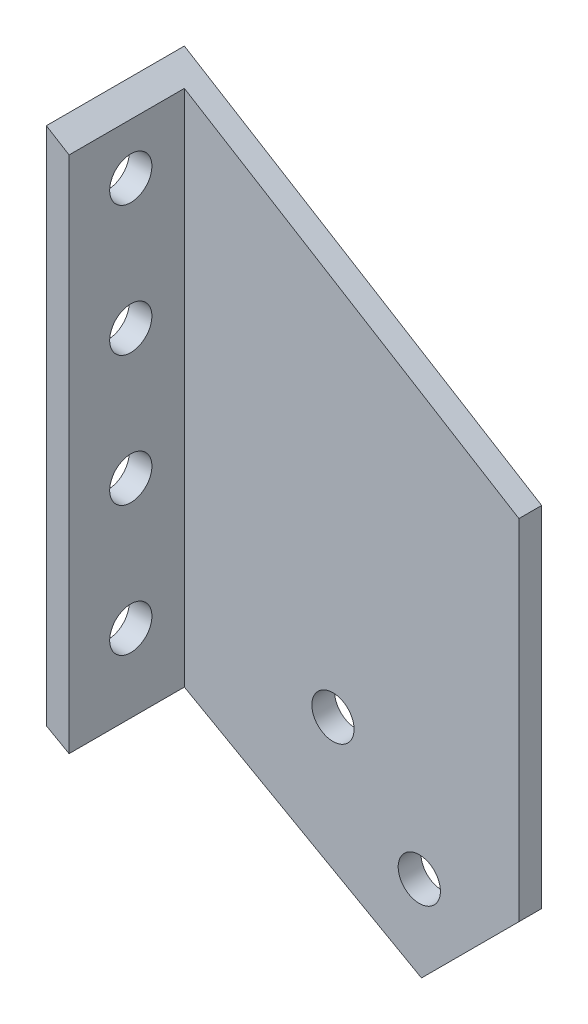
SolidWorks part; units mm, degrees
ref_plane "前视基准面" through (0, 0, 0) normal (0, 0, 1) x (1, 0, 0)
ref_plane "上视基准面" through (0, 0, 0) normal (0, 1, 0) x (1, 0, 0)
ref_plane "右视基准面" through (0, 0, 0) normal (1, 0, 0) x (0, 0, -1)
sketch "草图1" plane through (0, 0, 0) normal (0, 0, 1) x (1, 0, 0)
  line L0 (-1188.0651, 85.2964) -> (48811.9349, 85.2964) construction
  line L1 (-188.0651, -994.7583) -> (-188.0651, 49005.2417) construction
  line L2 (-1173.1343, -49.7036) -> (48826.8657, -49.7036) construction
  line L3 (-148.5651, -1041.5004) -> (-148.5651, 48958.4996) construction
  line L4 (-1169.9539, -234.7036) -> (48830.0461, -234.7036) construction
  line L5 (71.4349, -49.7036) -> (71.4349, -264.7036)
  line L6 (11.4349, -1089.7199) -> (11.4349, 48910.2801) construction
  line L7 (-972.3331, -324.7036) -> (49027.6669, -324.7036) construction
  line L8 (71.4349, -264.7036) -> (11.4349, -324.7036)
  line L9 (11.4349, -324.7036) -> (-148.5651, -234.7036)
  line L10 (-148.5651, -234.7036) -> (-148.5651, 85.2964)
  line L11 (-148.5651, 85.2964) -> (71.4349, -49.7036)
  line L12 (1811.9349, -49.7036) -> (1811.9349, -2299.7036) construction
  line L13 (1811.9349, -2299.7036) -> (-188.0651, -49.7036) construction
  circle A0 centre (-43.0651, -212.8286) radius 13
  circle A1 centre (10.084, -272.6213) radius 13
  point P15 (11.4349, -324.7036)
  point P17 (1811.9349, -49.7036)
  point P21 (-188.0651, -49.7036)
  point P24 (-43.0651, -212.8286)
  point P26 (10.084, -272.6213)
  dimension "D13" = 26
  dimension "D1" = 135
  dimension "D2" = 39.5
  dimension "D3" = 185
  dimension "D4" = 215
  dimension "D5" = 160
  dimension "D6" = 60
  dimension "D7" = 60
  dimension "D8" = 2000
  dimension "D9" = 2250
  dimension "D10" = 145
  dimension "D11" = 80
extrude "凸台-拉伸1" add sketch "草图1" along normal blind 14
sketch "草图2" plane through (0, 0, 14) normal (0, 0, 1) x (1, 0, 0)
  line L0 (-134.5651, 76.7055) -> (-134.5651, -242.5786)
  line L1 (71.4349, -49.7036) -> (-148.5651, 85.2964) construction
  line L2 (-148.5651, -234.7036) -> (11.4349, -324.7036) construction
  line L3 (-148.5651, 85.2964) -> (-148.5651, -234.7036) construction
  line L9 (71.4349, -49.7036) -> (-148.5651, 85.2964)
  line L10 (-148.5651, 85.2964) -> (-148.5651, -234.7036)
  line L11 (-148.5651, -234.7036) -> (11.4349, -324.7036)
  line L12 (11.4349, -324.7036) -> (71.4349, -264.7036)
  line L13 (71.4349, -264.7036) -> (71.4349, -49.7036)
  line L14 (-134.5651, 76.7055) -> (-148.5651, 85.2964)
  line L15 (-148.5651, 85.2964) -> (-148.5651, -234.7036)
  line L16 (-148.5651, -234.7036) -> (-134.5651, -242.5786)
  dimension "D1" = 14
  dimension "D2" = 0
extrude "凸台-拉伸2" add sketch "草图2" along normal blind 71
sketch "草图3" plane through (-148.5651, 0, 0) normal (-1, 0, 0) x (0, 0, 1)
  line L0 (47, -945.3498) -> (47, 49054.6502) construction
  line L1 (85, 85.2964) -> (85, -234.7036) construction
  line L2 (0, 45.2964) -> (85, 45.2964) construction
  line L3 (0, 85.2964) -> (0, -234.7036) construction
  line L4 (85, 85.2964) -> (0, 85.2964) construction
  circle A0 centre (47, 45.2964) radius 13
  dimension "D3" = 26
  dimension "D1" = 38
  dimension "D2" = 40
extrude "切除-拉伸1" cut sketch "草图3" against normal through all
pattern_linear "阵列(线性)1" count 4 spacing 80 along (0, -1, 0) of "切除-拉伸1"
